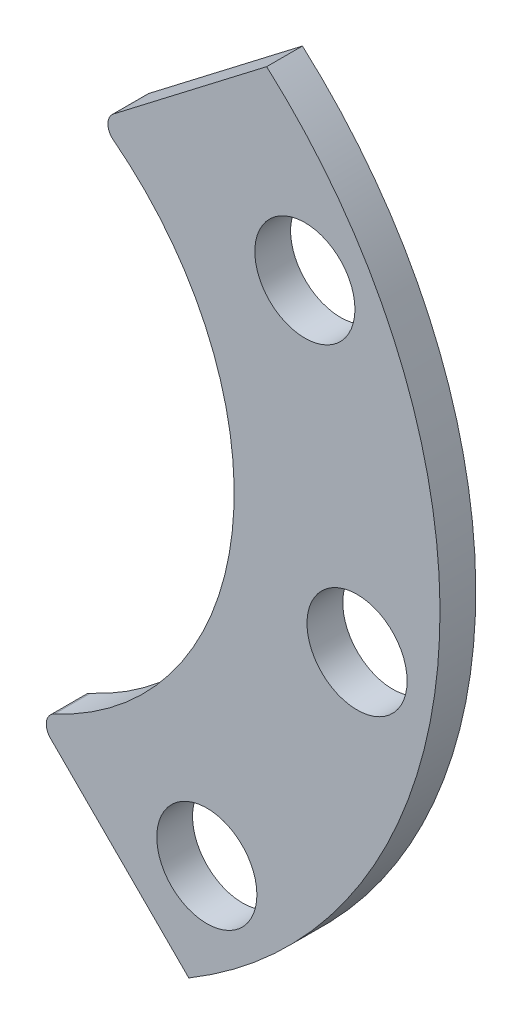
SolidWorks part; units mm, degrees
material "6061-T6 (SS)"
ref_plane "Front Plane" through (0, 0, 0) normal (0, 0, 1) x (1, 0, 0)
ref_plane "Top Plane" through (0, 0, 0) normal (0, 1, 0) x (1, 0, 0)
ref_plane "Right Plane" through (0, 0, 0) normal (1, 0, 0) x (0, 0, -1)
sketch "Sketch6" plane through (0, 0, 0) normal (0, 0, 1) x (1, 0, 0)
  line L2 (23.4707, -39.2969) -> (11.181, -27.0044)
  line L3 (16.7799, 23.7965) -> (30.3812, 34.236)
  circle A6 centre (25.0687, -29.8757) radius 4.445
  circle A7 centre (33.775, 19.5) radius 4.445
  arc A8 (30.3812, 34.236) -> (23.4707, -39.2969) centre (0, 0) cw
  circle A9 centre (25.0687, -29.8757) radius 6.5
  circle A10 centre (38.4075, -6.7723) radius 6.5
  arc A11 (11.5459, -24.9539) -> (11.181, -27.0044) centre (12.0792, -26.1065) ccw
  arc A12 (11.5459, -24.9539) -> (16.7782, 21.7829) centre (0, 0) ccw
  arc A13 (16.7799, 23.7965) -> (16.7782, 21.7829) centre (17.5531, 22.7891) ccw
  circle A14 centre (38.4075, -6.7723) radius 4.445
  circle A15 centre (33.775, 19.5) radius 6.5
  point P13 (0, 0)
  point P17 (0, 0)
  point P23 (0, 0)
  point P24 (0, 0)
  point P25 (76.3637, -73.0158)
  point P27 (0, 0)
  dimension "D1" = 25.0687
  dimension "D2" = 29.8757
  dimension "D3" = 38.4075
  dimension "D4" = 6.7723
  dimension "D5" = 33.775
  dimension "D6" = 19.5
extrude "Boss-Extrude3" add sketch "Sketch6" along normal blind 3.175 contours A9 A6 | L3 A13 A12 A11 L2 A8 A15 A9 A10 | A10 A14 | A15 A7
